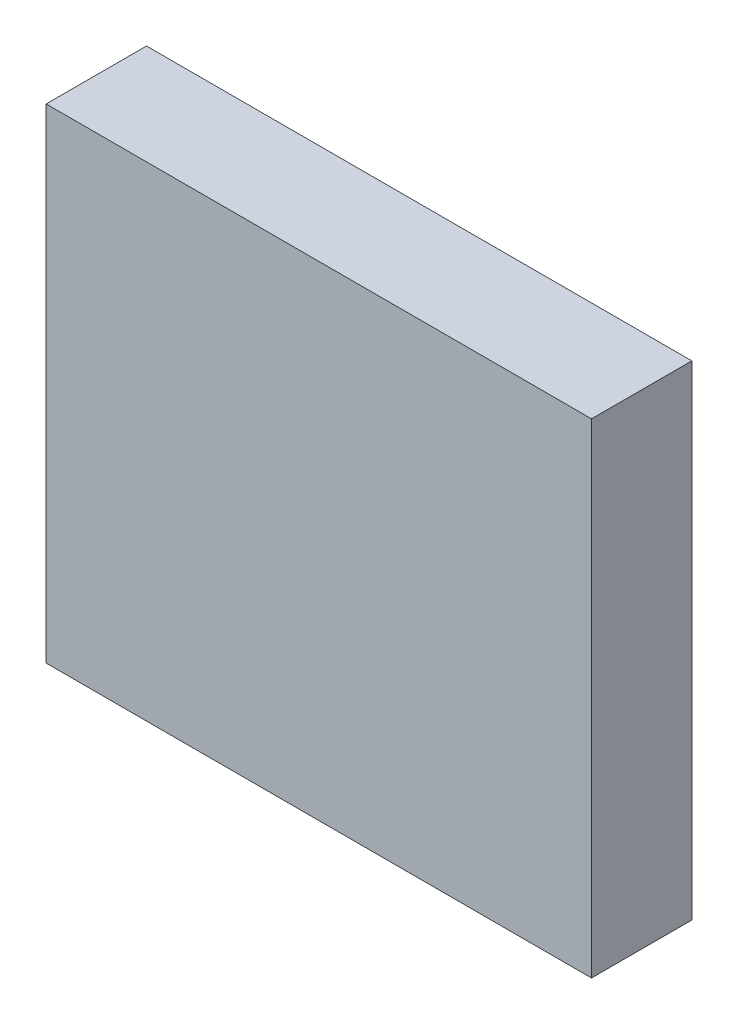
SolidWorks part; units mm, degrees
ref_plane "正面" through (0, 0, 0) normal (0, 0, 1) x (1, 0, 0)
ref_plane "平面" through (0, 0, 0) normal (0, 1, 0) x (1, 0, 0)
ref_plane "右側面" through (0, 0, 0) normal (1, 0, 0) x (0, 0, -1)
sketch "ｽｹｯﾁ1" plane through (0, 0, 0) normal (0, 0, 1) x (1, 0, 0)
  line L0 (-45, 0) -> (45, 0) construction
  line L1 (-45, 45) -> (45, 45)
  line L2 (-45, 45) -> (-45, -45)
  line L3 (-45, -45) -> (45, -45)
  line L4 (45, 45) -> (45, -45)
  line L5 (0, -45) -> (0, 45) construction
  point P8 (0, 0)
  dimension "D1" = 90
  dimension "D2" = 90
  dimension "D3" = 0
  dimension "D4" = 0
extrude "ﾎﾞｽ - 押し出し1" add sketch "ｽｹｯﾁ1" along normal blind 1.6
sketch "ｽｹｯﾁ4" plane through (0, 0, 0) normal (0, 0, -1) x (-1, 0, 0)
  line L0 (-45, -45) -> (-45, 45) construction
  line L1 (-23.89, -36.1) -> (-6.11, -36.1)
  line L2 (-23.89, -36.1) -> (-23.89, -44.6)
  line L3 (-23.89, -44.6) -> (-6.11, -44.6)
  line L4 (-6.11, -36.1) -> (-6.11, -44.6)
  line L6 (45, 45) -> (45, -45) construction
  line L8 (-38.85, 26.89) -> (-36.35, 26.89)
  line L9 (-38.85, 26.89) -> (-38.85, 9.11)
  line L10 (-38.85, 9.11) -> (-36.35, 9.11)
  line L11 (-36.35, 26.89) -> (-36.35, 9.11)
  line L12 (16.11, 44.6) -> (33.89, 44.6)
  line L13 (16.11, 44.6) -> (16.11, 36.1)
  line L14 (16.11, 36.1) -> (33.89, 36.1)
  line L15 (33.89, 44.6) -> (33.89, 36.1)
  line L16 (-45, 45) -> (45, 45) construction
  line L17 (45, -45) -> (-45, -45) construction
  line L18 (36.1, 26.89) -> (44.6, 26.89)
  line L19 (36.1, 26.89) -> (36.1, 9.11)
  line L20 (36.1, 9.11) -> (44.6, 9.11)
  line L21 (44.6, 26.89) -> (44.6, 9.11)
  point P6 (25, 44.6)
  point P7 (-15, -44.6)
  point P14 (-38.85, 18)
  point P15 (-37.6, 9.11)
  point P25 (44.6, 18)
  dimension "D2" = 8.5
  dimension "D3" = 8.5
  dimension "D4" = 17.78
  dimension "D5" = 2.5
  dimension "D6" = 17.78
  dimension "D7" = 27
  dimension "D8" = 7.4
  dimension "D9" = 20
  dimension "D10" = 30
  dimension "D11" = 0.4
  dimension "D12" = 17.78
  dimension "D13" = 17.78
  dimension "D14" = 0.4
  dimension "D15" = 27
  dimension "D16" = 8.5
  dimension "D17" = 0.4
extrude "ﾎﾞｽ - 押し出し2" add sketch "ｽｹｯﾁ4" along normal blind 2.5
sketch "ｽｹｯﾁ5" plane through (0, 0, -2.5) normal (0, 0, -1) x (-1, 0, 0)
  line L8 (-38.85, 9.11) -> (-36.35, 9.11) construction
  line L33 (-37.92, 18.32) -> (-37.28, 18.32)
  line L34 (-37.92, 18.32) -> (-37.92, 17.68)
  line L35 (-37.92, 17.68) -> (-37.28, 17.68)
  line L36 (-37.28, 18.32) -> (-37.28, 17.68)
  line L37 (-38.85, 26.89) -> (-38.85, 9.11) construction
  line L39 (-37.92, 15.78) -> (-37.28, 15.78)
  line L40 (-37.92, 15.78) -> (-37.92, 15.14)
  line L41 (-37.92, 15.14) -> (-37.28, 15.14)
  line L42 (-37.28, 15.78) -> (-37.28, 15.14)
  line L45 (-37.92, 13.24) -> (-37.28, 13.24)
  line L46 (-37.92, 13.24) -> (-37.92, 12.6)
  line L47 (-37.92, 12.6) -> (-37.28, 12.6)
  line L48 (-37.28, 13.24) -> (-37.28, 12.6)
  line L49 (-37.92, 10.7) -> (-37.28, 10.7)
  line L50 (-37.92, 10.7) -> (-37.92, 10.06)
  line L51 (-37.92, 10.06) -> (-37.28, 10.06)
  line L52 (-37.28, 10.7) -> (-37.28, 10.06)
  line L53 (-37.92, 20.86) -> (-37.28, 20.86)
  line L54 (-37.92, 20.86) -> (-37.92, 20.22)
  line L55 (-37.92, 20.22) -> (-37.28, 20.22)
  line L56 (-37.28, 20.86) -> (-37.28, 20.22)
  line L57 (-37.92, 23.4) -> (-37.28, 23.4)
  line L58 (-37.92, 23.4) -> (-37.92, 22.76)
  line L59 (-37.92, 22.76) -> (-37.28, 22.76)
  line L60 (-37.28, 23.4) -> (-37.28, 22.76)
  line L61 (-37.92, 25.94) -> (-37.28, 25.94)
  line L62 (-37.92, 25.94) -> (-37.92, 25.3)
  line L63 (-37.92, 25.3) -> (-37.28, 25.3)
  line L64 (-37.28, 25.94) -> (-37.28, 25.3)
  point P47 (-37.6, 17.68)
  point P50 (-37.6, 9.11)
  point P53 (-37.92, 18)
  point P54 (-38.85, 18)
  point P59 (-37.28, 15.46)
  point P60 (-37.28, 18)
  point P61 (-37.28, 12.92)
  point P70 (-37.28, 10.38)
  point P83 (-37.28, 20.54)
  point P84 (-37.28, 23.08)
  point P85 (-37.28, 25.62)
  point P179 (-37.6, 10.7)
  point P180 (-37.6, 13.24)
  point P181 (-37.6, 15.78)
  point P182 (-37.6, 18.32)
  point P183 (-37.6, 20.86)
  point P184 (-37.6, 23.4)
  point P185 (-37.6, 25.94)
  dimension "D21" = 0.64
  dimension "D22" = 0.64
  dimension "D23" = 0.64
  dimension "D24" = 0.64
  dimension "D25" = 2.54
  dimension "D26" = 0.64
  dimension "D27" = 2.54
  dimension "D28" = 0.64
  dimension "D29" = 2.54
  dimension "D30" = 0.64
  dimension "D31" = 0.64
  dimension "D32" = 0.64
  dimension "D33" = 0.64
  dimension "D34" = 2.54
  dimension "D35" = 2.54
  dimension "D36" = 0.64
  dimension "D37" = 0.64
  dimension "D38" = 0.64
  dimension "D39" = 2.54
  dimension "D40" = 0.64
extrude "ﾎﾞｽ - 押し出し3" add sketch "ｽｹｯﾁ5" along normal blind 6.1
sketch "ｽｹｯﾁ6" plane through (0, 0, 1.6) normal (0, 0, 1) x (1, 0, 0)
  line L0 (-45, -45) -> (45, -45) construction
  line L1 (-41.74, -33.26) -> (-38.26, -33.26)
  line L2 (-41.74, -33.26) -> (-41.74, -36.74)
  line L3 (-41.74, -36.74) -> (-38.26, -36.74)
  line L4 (-38.26, -33.26) -> (-38.26, -36.74)
  line L5 (-45, 45) -> (-45, -45) construction
  line L6 (45, 45) -> (-45, 45) construction
  line L7 (-41.74, 36.74) -> (-38.26, 36.74)
  line L8 (-41.74, 36.74) -> (-41.74, 33.26)
  line L9 (-41.74, 33.26) -> (-38.26, 33.26)
  line L10 (-38.26, 36.74) -> (-38.26, 33.26)
  line L11 (45, -45) -> (45, 45) construction
  line L12 (28.26, -33.26) -> (31.74, -33.26)
  line L13 (28.26, -33.26) -> (28.26, -36.74)
  line L14 (28.26, -36.74) -> (31.74, -36.74)
  line L15 (31.74, -33.26) -> (31.74, -36.74)
  line L17 (28.26, 36.74) -> (31.74, 36.74)
  line L18 (28.26, 36.74) -> (28.26, 33.26)
  line L19 (28.26, 33.26) -> (31.74, 33.26)
  line L20 (31.74, 36.74) -> (31.74, 33.26)
  point P4 (-41.74, -35)
  point P7 (-40, -36.74)
  point P14 (-41.74, 35)
  point P17 (-40, 36.74)
  point P22 (30, -36.74)
  point P25 (31.74, -35)
  point P30 (30, 36.74)
  point P31 (31.74, 35)
  dimension "D1" = 3.48
  dimension "D2" = 3.48
  dimension "D3" = 10
  dimension "D4" = 5
  dimension "D5" = 3.48
  dimension "D6" = 3.48
  dimension "D7" = 10
  dimension "D8" = 5
  dimension "D9" = 15
  dimension "D10" = 10
  dimension "D11" = 3.48
  dimension "D12" = 3.48
  dimension "D13" = 15
  dimension "D14" = 10
  dimension "D15" = 3.48
  dimension "D16" = 3.48
extrude "ﾎﾞｽ - 押し出し4" add sketch "ｽｹｯﾁ6" along normal blind 2
sketch "ｽｹｯﾁ7" plane through (0, 0, 1.6) normal (0, 0, 1) x (1, 0, 0)
  line L0 (-45, -45) -> (45, -45) construction
  line L1 (-41, 2) -> (-39, 2)
  line L2 (-41, 2) -> (-41, -2)
  line L3 (-41, -2) -> (-39, -2)
  line L4 (-39, 2) -> (-39, -2)
  line L5 (-45, 45) -> (-45, -45) construction
  line L6 (45, -45) -> (45, 45) construction
  line L7 (29, 2) -> (31, 2)
  line L8 (29, 2) -> (29, -2)
  line L9 (29, -2) -> (31, -2)
  line L10 (31, 2) -> (31, -2)
  line L11 (45, 45) -> (-45, 45) construction
  line L12 (-7, 36) -> (-3, 36)
  line L13 (-7, 36) -> (-7, 34)
  line L14 (-7, 34) -> (-3, 34)
  line L15 (-3, 36) -> (-3, 34)
  line L17 (-7, -34) -> (-3, -34)
  line L18 (-7, -34) -> (-7, -36)
  line L19 (-7, -36) -> (-3, -36)
  line L20 (-3, -34) -> (-3, -36)
  line L21 (-6, 2) -> (-4, 2)
  line L22 (-6, 2) -> (-6, -2)
  line L23 (-6, -2) -> (-4, -2)
  line L24 (-4, 2) -> (-4, -2)
  point P4 (-41, 0)
  point P7 (-40, -2)
  point P14 (30, 2)
  point P17 (31, 0)
  point P22 (-7, 35)
  point P25 (-5, 36)
  point P30 (-7, -35)
  point P31 (-5, -36)
  point P36 (-4, 0)
  point P37 (29, 0)
  point P38 (-5, 34)
  point P39 (-5, 2)
  dimension "D1" = 4
  dimension "D2" = 2
  dimension "D3" = 45
  dimension "D4" = 5
  dimension "D5" = 4
  dimension "D6" = 2
  dimension "D7" = 15
  dimension "D8" = 45
  dimension "D9" = 4
  dimension "D10" = 2
  dimension "D11" = 10
  dimension "D12" = 40
  dimension "D13" = 4
  dimension "D14" = 2
  dimension "D15" = 10
  dimension "D16" = 40
  dimension "D17" = 4
  dimension "D18" = 2
extrude "ﾎﾞｽ - 押し出し5" add sketch "ｽｹｯﾁ7" along normal blind 1.1
sketch "ｽｹｯﾁ8" plane through (0, 0, 1.6) normal (0, 0, 1) x (1, 0, 0)
  line L1 (7.3, 7.6) -> (14.7, 7.6)
  line L2 (7.3, 7.6) -> (7.3, -7.6)
  line L3 (7.3, -7.6) -> (14.7, -7.6)
  line L4 (14.7, 7.6) -> (14.7, -7.6)
  line L5 (-45, 45) -> (-45, -45) construction
  point P4 (7.3, 0)
  point P11 (-45, 0)
  point P12 (11, 7.6)
  dimension "D1" = 15.2
  dimension "D2" = 7.4
  dimension "D3" = 56
extrude "ﾎﾞｽ - 押し出し6" add sketch "ｽｹｯﾁ8" along normal blind 2.65
sketch "ｽｹｯﾁ9" plane through (0, -44.6, 0) normal (0, -1, 0) x (1, 0, 0)
  line L1 (14.68, -0.93) -> (15.32, -0.93)
  line L2 (14.68, -0.93) -> (14.68, -1.57)
  line L3 (14.68, -1.57) -> (15.32, -1.57)
  line L4 (15.32, -0.93) -> (15.32, -1.57)
  line L5 (6.11, -2.5) -> (6.11, 0) construction
  line L6 (6.11, -1.25) -> (23.89, -1.25) construction
  line L7 (23.89, -2.5) -> (23.89, 0) construction
  line L8 (23.89, -2.5) -> (6.11, -2.5) construction
  line L10 (15, -2.5) -> (15, 0) construction
  line L11 (23.89, 0) -> (6.11, 0) construction
  line L13 (12.14, -0.93) -> (12.78, -0.93)
  line L14 (12.14, -0.93) -> (12.14, -1.57)
  line L15 (12.14, -1.57) -> (12.78, -1.57)
  line L16 (12.78, -0.93) -> (12.78, -1.57)
  line L17 (9.6, -0.93) -> (10.24, -0.93)
  line L18 (9.6, -0.93) -> (9.6, -1.57)
  line L19 (9.6, -1.57) -> (10.24, -1.57)
  line L20 (10.24, -0.93) -> (10.24, -1.57)
  line L21 (7.06, -0.93) -> (7.7, -0.93)
  line L22 (7.06, -0.93) -> (7.06, -1.57)
  line L23 (7.06, -1.57) -> (7.7, -1.57)
  line L24 (7.7, -0.93) -> (7.7, -1.57)
  line L25 (17.22, -0.93) -> (17.86, -0.93)
  line L26 (17.22, -0.93) -> (17.22, -1.57)
  line L27 (17.22, -1.57) -> (17.86, -1.57)
  line L28 (17.86, -0.93) -> (17.86, -1.57)
  line L29 (19.76, -0.93) -> (20.4, -0.93)
  line L30 (19.76, -0.93) -> (19.76, -1.57)
  line L31 (19.76, -1.57) -> (20.4, -1.57)
  line L32 (20.4, -0.93) -> (20.4, -1.57)
  line L33 (22.3, -0.93) -> (22.94, -0.93)
  line L34 (22.3, -0.93) -> (22.3, -1.57)
  line L35 (22.3, -1.57) -> (22.94, -1.57)
  line L36 (22.94, -0.93) -> (22.94, -1.57)
  point P10 (15.32, -1.25)
  point P13 (15, -1.57)
  point P42 (12.46, -1.57)
  point P43 (9.92, -1.57)
  point P44 (12.14, -1.25)
  point P46 (9.6, -1.25)
  point P47 (7.06, -1.25)
  point P48 (7.38, -1.57)
  point P49 (17.54, -1.57)
  point P50 (20.08, -1.57)
  point P51 (22.62, -1.57)
  point P52 (17.22, -1.25)
  point P53 (19.76, -1.25)
  point P54 (22.3, -1.25)
  dimension "D1" = 0.64
  dimension "D2" = 0.64
  dimension "D3" = 0.64
  dimension "D4" = 0.64
  dimension "D5" = 0.64
  dimension "D6" = 0.64
  dimension "D7" = 0.64
  dimension "D8" = 0.64
  dimension "D9" = 0.64
  dimension "D10" = 0.64
  dimension "D11" = 0.64
  dimension "D12" = 2.54
  dimension "D13" = 2.54
  dimension "D14" = 2.54
  dimension "D15" = 0.64
  dimension "D16" = 0.64
  dimension "D17" = 0.64
  dimension "D18" = 2.54
  dimension "D19" = 2.54
  dimension "D20" = 2.54
extrude "ｶｯﾄ - 押し出し1" cut sketch "ｽｹｯﾁ9" against normal blind 7.5
sketch "ｽｹｯﾁ10" plane through (-44.6, 0, 0) normal (-1, 0, 0) x (0, 0, 1)
  line L0 (-1.25, 26.89) -> (-1.25, 9.11) construction
  line L1 (-2.5, 26.89) -> (0, 26.89) construction
  line L2 (-2.5, 9.11) -> (0, 9.11) construction
  line L3 (-2.5, 18) -> (0, 18) construction
  line L4 (-2.5, 9.11) -> (-2.5, 26.89) construction
  line L5 (0, 9.11) -> (0, 26.89) construction
  line L7 (-1.57, 18.32) -> (-0.93, 18.32)
  line L8 (-1.57, 18.32) -> (-1.57, 17.68)
  line L9 (-1.57, 17.68) -> (-0.93, 17.68)
  line L10 (-0.93, 18.32) -> (-0.93, 17.68)
  line L11 (-1.57, 25.94) -> (-0.93, 25.94)
  line L12 (-1.57, 25.94) -> (-1.57, 25.3)
  line L13 (-1.57, 25.3) -> (-0.93, 25.3)
  line L14 (-0.93, 25.94) -> (-0.93, 25.3)
  line L15 (-1.57, 23.4) -> (-0.93, 23.4)
  line L16 (-1.57, 23.4) -> (-1.57, 22.76)
  line L17 (-1.57, 22.76) -> (-0.93, 22.76)
  line L18 (-0.93, 23.4) -> (-0.93, 22.76)
  line L19 (-1.57, 20.86) -> (-0.93, 20.86)
  line L20 (-1.57, 20.86) -> (-1.57, 20.22)
  line L21 (-1.57, 20.22) -> (-0.93, 20.22)
  line L22 (-0.93, 20.86) -> (-0.93, 20.22)
  line L23 (-1.57, 15.78) -> (-0.93, 15.78)
  line L24 (-1.57, 15.78) -> (-1.57, 15.14)
  line L25 (-1.57, 15.14) -> (-0.93, 15.14)
  line L26 (-0.93, 15.78) -> (-0.93, 15.14)
  line L27 (-1.57, 13.24) -> (-0.93, 13.24)
  line L28 (-1.57, 13.24) -> (-1.57, 12.6)
  line L29 (-1.57, 12.6) -> (-0.93, 12.6)
  line L30 (-0.93, 13.24) -> (-0.93, 12.6)
  line L31 (-1.57, 10.7) -> (-0.93, 10.7)
  line L32 (-1.57, 10.7) -> (-1.57, 10.06)
  line L33 (-1.57, 10.06) -> (-0.93, 10.06)
  line L34 (-0.93, 10.7) -> (-0.93, 10.06)
  point P16 (-1.25, 18.32)
  point P17 (-1.57, 18)
  point P30 (-1.57, 20.54)
  point P31 (-0.93, 23.08)
  point P32 (-0.93, 20.54)
  point P33 (-0.93, 25.62)
  point P34 (-1.25, 20.86)
  point P35 (-1.25, 23.4)
  point P36 (-1.25, 25.94)
  point P49 (-0.93, 15.46)
  point P50 (-0.93, 12.92)
  point P51 (-0.93, 10.38)
  dimension "D1" = 0.64
  dimension "D2" = 0.64
  dimension "D3" = 0.64
  dimension "D4" = 0.64
  dimension "D5" = 0.64
  dimension "D6" = 2.54
  dimension "D7" = 2.54
  dimension "D8" = 2.54
  dimension "D9" = 0.64
  dimension "D10" = 0.64
  dimension "D11" = 0.64
  dimension "D12" = 0.64
  dimension "D13" = 0.64
  dimension "D14" = 0.64
  dimension "D15" = 2.54
  dimension "D16" = 2.54
  dimension "D17" = 2.54
  dimension "D18" = 0.64
  dimension "D19" = 0.64
  dimension "D20" = 0.64
extrude "ｶｯﾄ - 押し出し2" cut sketch "ｽｹｯﾁ10" against normal blind 7.5
sketch "ｽｹｯﾁ11" plane through (0, 44.6, 0) normal (0, 1, 0) x (1, 0, 0)
  line L0 (-33.89, 1.25) -> (-16.11, 1.25) construction
  line L1 (-33.89, 2.5) -> (-33.89, 0) construction
  line L2 (-16.11, 2.5) -> (-16.11, 0) construction
  line L3 (-25, 2.5) -> (-25, 0) construction
  line L4 (-33.89, 2.5) -> (-16.11, 2.5) construction
  line L5 (45, 0) -> (-45, 0) construction
  line L7 (-25.32, 1.57) -> (-24.68, 1.57)
  line L8 (-25.32, 1.57) -> (-25.32, 0.93)
  line L9 (-25.32, 0.93) -> (-24.68, 0.93)
  line L10 (-24.68, 1.57) -> (-24.68, 0.93)
  line L11 (-32.94, 1.57) -> (-32.3, 1.57)
  line L12 (-32.94, 1.57) -> (-32.94, 0.93)
  line L13 (-32.94, 0.93) -> (-32.3, 0.93)
  line L14 (-32.3, 1.57) -> (-32.3, 0.93)
  line L15 (-30.4, 1.57) -> (-29.76, 1.57)
  line L16 (-30.4, 1.57) -> (-30.4, 0.93)
  line L17 (-30.4, 0.93) -> (-29.76, 0.93)
  line L18 (-29.76, 1.57) -> (-29.76, 0.93)
  line L19 (-27.86, 1.57) -> (-27.22, 1.57)
  line L20 (-27.86, 1.57) -> (-27.86, 0.93)
  line L21 (-27.86, 0.93) -> (-27.22, 0.93)
  line L22 (-27.22, 1.57) -> (-27.22, 0.93)
  line L23 (-22.78, 1.57) -> (-22.14, 1.57)
  line L24 (-22.78, 1.57) -> (-22.78, 0.93)
  line L25 (-22.78, 0.93) -> (-22.14, 0.93)
  line L26 (-22.14, 1.57) -> (-22.14, 0.93)
  line L27 (-20.24, 1.57) -> (-19.6, 1.57)
  line L28 (-20.24, 1.57) -> (-20.24, 0.93)
  line L29 (-20.24, 0.93) -> (-19.6, 0.93)
  line L30 (-19.6, 1.57) -> (-19.6, 0.93)
  line L31 (-17.7, 1.57) -> (-17.06, 1.57)
  line L32 (-17.7, 1.57) -> (-17.7, 0.93)
  line L33 (-17.7, 0.93) -> (-17.06, 0.93)
  line L34 (-17.06, 1.57) -> (-17.06, 0.93)
  point P16 (-25, 0.93)
  point P17 (-24.68, 1.25)
  point P42 (-27.54, 1.57)
  point P43 (-30.08, 1.57)
  point P44 (-32.62, 1.57)
  point P45 (-32.94, 1.25)
  point P46 (-30.4, 1.25)
  point P47 (-27.86, 1.25)
  point P48 (-22.46, 1.57)
  point P49 (-19.92, 1.57)
  point P50 (-17.38, 1.57)
  point P52 (-22.78, 1.25)
  point P53 (-20.24, 1.25)
  point P54 (-17.7, 1.25)
  dimension "D1" = 0.64
  dimension "D2" = 0.64
  dimension "D3" = 0.64
  dimension "D4" = 0.64
  dimension "D5" = 0.64
  dimension "D6" = 2.54
  dimension "D7" = 2.54
  dimension "D8" = 2.54
  dimension "D9" = 0.64
  dimension "D10" = 0.64
  dimension "D11" = 0.64
  dimension "D12" = 0.64
  dimension "D13" = 0.64
  dimension "D14" = 0.64
  dimension "D15" = 0.64
  dimension "D16" = 0.64
  dimension "D17" = 0.64
  dimension "D18" = 2.54
  dimension "D19" = 2.54
  dimension "D20" = 2.54
extrude "ｶｯﾄ - 押し出し3" cut sketch "ｽｹｯﾁ11" against normal blind 7.5
sketch "ｽｹｯﾁ14" plane through (0, 0, -2.5) normal (0, 0, -1) x (-1, 0, 0)
  line L6 (46.35, 45) -> (-55, 45)
  line L7 (46.35, 45) -> (46.35, -45)
  line L8 (46.35, -45) -> (-55, -45)
  line L9 (-55, 45) -> (-55, -45)
  point P5 (46.35, 0)
  dimension "D1" = 46.35
  dimension "D2" = 90
  dimension "D3" = 55
extrude "ﾎﾞｽ - 押し出し9" add sketch "ｽｹｯﾁ14" against normal blind 18.65 separate body
